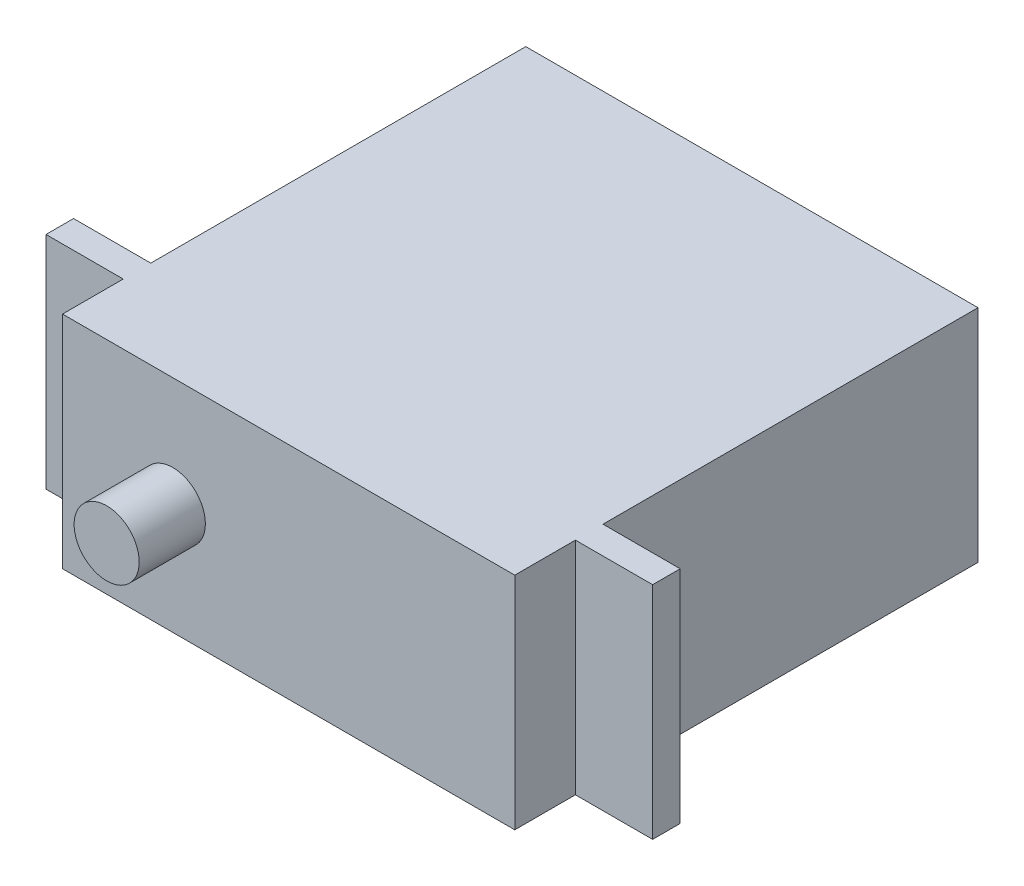
SolidWorks part; units mm, degrees
ref_plane "正面" through (0, 0, 0) normal (0, 0, 1) x (1, 0, 0)
ref_plane "平面" through (0, 0, 0) normal (0, 1, 0) x (1, 0, 0)
ref_plane "右側面" through (0, 0, 0) normal (1, 0, 0) x (0, 0, -1)
sketch "ｽｹｯﾁ1" plane through (0, 0, 0) normal (0, 0, 1) x (1, 0, 0)
  line L1 (-44.7516, -3.4357) -> (-3.7516, -3.4357)
  line L2 (-44.7516, -3.4357) -> (-44.7516, -23.4357)
  line L3 (-44.7516, -23.4357) -> (-3.7516, -23.4357)
  line L4 (-3.7516, -3.4357) -> (-3.7516, -23.4357)
  dimension "D1" = 20
  dimension "D2" = 41
  dimension "D3" = 20
  dimension "D4" = 41
extrude "ﾎﾞｽ - 押し出し1" add sketch "ｽｹｯﾁ1" along normal blind 42
sketch "ｽｹｯﾁ3" plane through (-3.7516, 0, 0) normal (1, 0, 0) x (0, 0, -1)
  line L0 (-42, -3.4357) -> (0, -3.4357) construction
  line L1 (-36.5, -3.4357) -> (-34, -3.4357)
  line L2 (-36.5, -3.4357) -> (-36.5, -23.4357)
  line L3 (-36.5, -23.4357) -> (-34, -23.4357)
  line L4 (-34, -3.4357) -> (-34, -23.4357)
  line L5 (-42, -23.4357) -> (0, -23.4357) construction
  line L7 (-42, -23.4357) -> (-42, -3.4357) construction
  dimension "D1" = 20
  dimension "D2" = 2.5
  dimension "D3" = 2.5
  dimension "D4" = 5.5
extrude "ﾎﾞｽ - 押し出し2" add sketch "ｽｹｯﾁ3" along normal blind 7
sketch "ｽｹｯﾁ4" plane through (-44.7516, 0, 0) normal (-1, 0, 0) x (0, 0, 1)
  line L0 (42, -3.4357) -> (0, -3.4357) construction
  line L1 (34, -3.4357) -> (36.5, -3.4357)
  line L2 (34, -3.4357) -> (34, -23.4357)
  line L3 (34, -23.4357) -> (36.5, -23.4357)
  line L4 (36.5, -3.4357) -> (36.5, -23.4357)
  line L5 (42, -23.4357) -> (0, -23.4357) construction
  line L6 (42, -3.4357) -> (42, -23.4357) construction
  dimension "D1" = 20
  dimension "D2" = 2.5
  dimension "D3" = 2.5
  dimension "D4" = 5.5
extrude "ﾎﾞｽ - 押し出し3" add sketch "ｽｹｯﾁ4" along normal blind 7
sketch "ｽｹｯﾁ5" plane through (0, 0, 42) normal (0, 0, 1) x (1, 0, 0)
  line L0 (-34.7516, -13.4357) -> (-34.7516, -3.4357) construction
  line L1 (-3.7516, -3.4357) -> (-44.7516, -3.4357) construction
  line L2 (-34.7516, -13.4357) -> (-34.7516, -23.4357) construction
  line L3 (-44.7516, -23.4357) -> (-3.7516, -23.4357) construction
  line L4 (-34.7516, -13.4357) -> (-44.7516, -13.4357) construction
  line L5 (-44.7516, -3.4357) -> (-44.7516, -23.4357) construction
  circle A0 centre (-34.7516, -13.4357) radius 2.95
  dimension "D1" = 5.9
  dimension "D2" = 10
extrude "ﾎﾞｽ - 押し出し4" add sketch "ｽｹｯﾁ5" along normal blind 6
